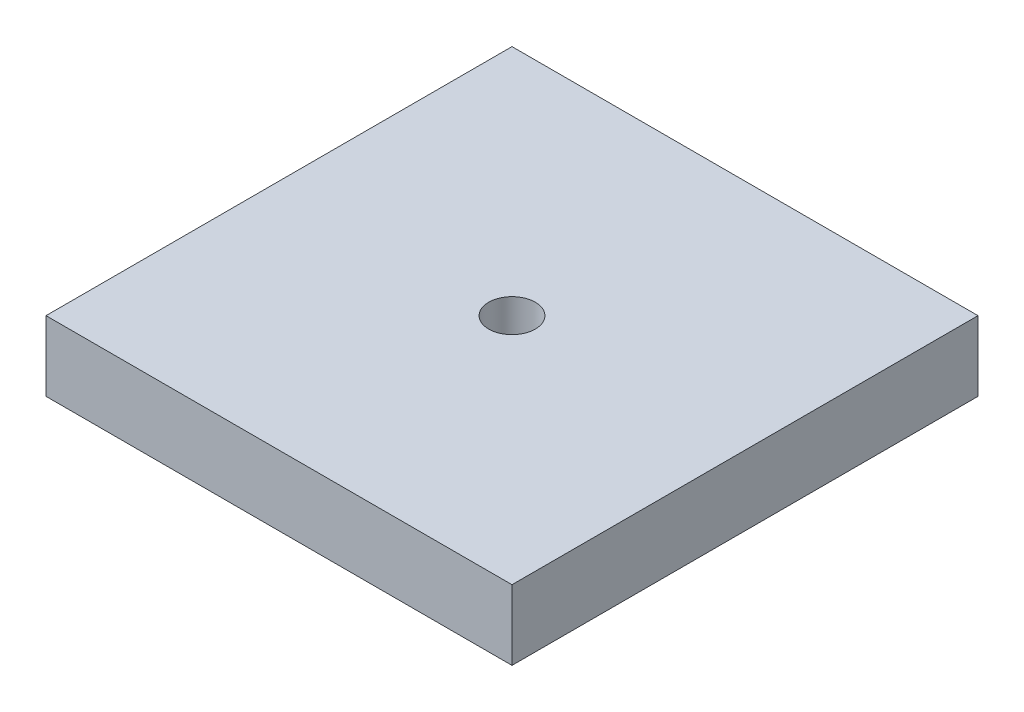
SolidWorks part; units mm, degrees
ref_plane "Front Plane" through (0, 0, 0) normal (0, 0, 1) x (1, 0, 0)
ref_plane "Top Plane" through (0, 0, 0) normal (0, 1, 0) x (1, 0, 0)
ref_plane "Right Plane" through (0, 0, 0) normal (1, 0, 0) x (0, 0, -1)
sketch "Sketch1" plane through (0, 0, 0) normal (0, 1, 0) x (1, 0, 0)
  line L1 (-127, 127) -> (127, 127)
  line L2 (-127, 127) -> (-127, -127)
  line L3 (-127, -127) -> (127, -127)
  line L4 (127, 127) -> (127, -127)
  line L5 (-127, 127) -> (127, -127) construction
  line L6 (-127, -127) -> (127, 127) construction
  circle A0 centre (0, 0) radius 12.7
  point P0 (0, 0)
  dimension "D3" = 25.4
  dimension "D1" = 254
  dimension "D2" = 254
extrude "Boss-Extrude2" add sketch "Sketch1" along normal blind 38.1 contours L2 L1 L4 L3
